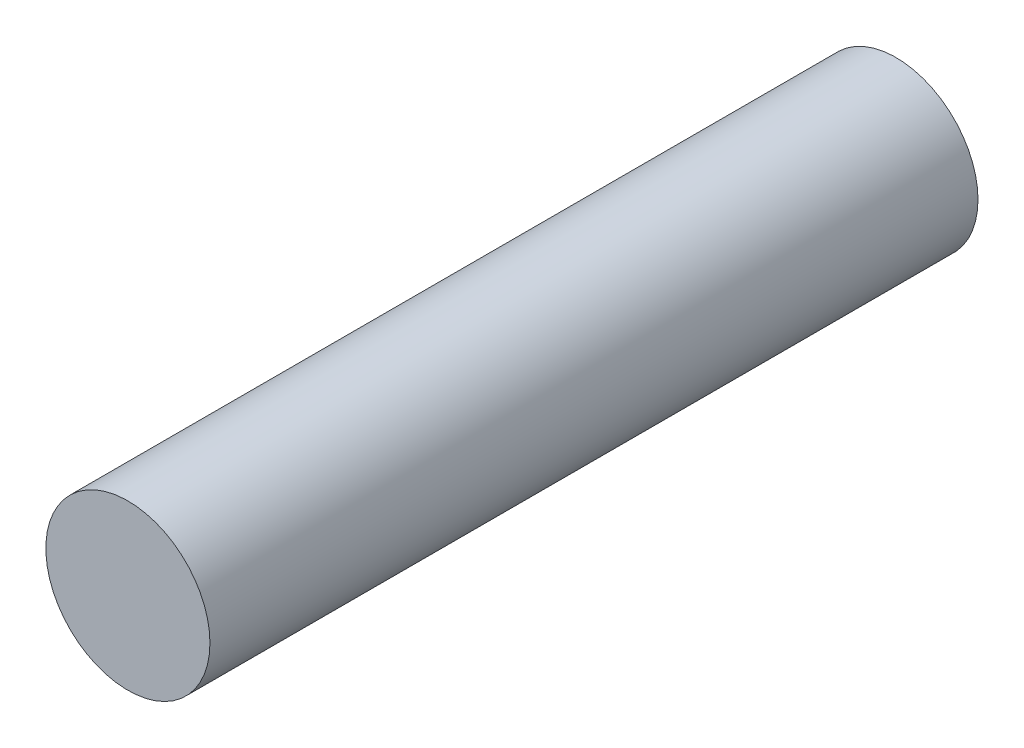
SolidWorks part; units mm, degrees
material "6061-T6 (SS)"
ref_plane "Front Plane" through (0, 0, 0) normal (0, 0, 1) x (1, 0, 0)
ref_plane "Top Plane" through (0, 0, 0) normal (0, 1, 0) x (1, 0, 0)
ref_plane "Right Plane" through (0, 0, 0) normal (1, 0, 0) x (0, 0, -1)
sketch "Body sketch" plane through (0, 0, 0) normal (0, 0, 1) x (1, 0, 0)
  circle A0 centre (0, 0) radius 2.5
extrude "Body" add sketch "Body sketch" along normal blind 23.4
